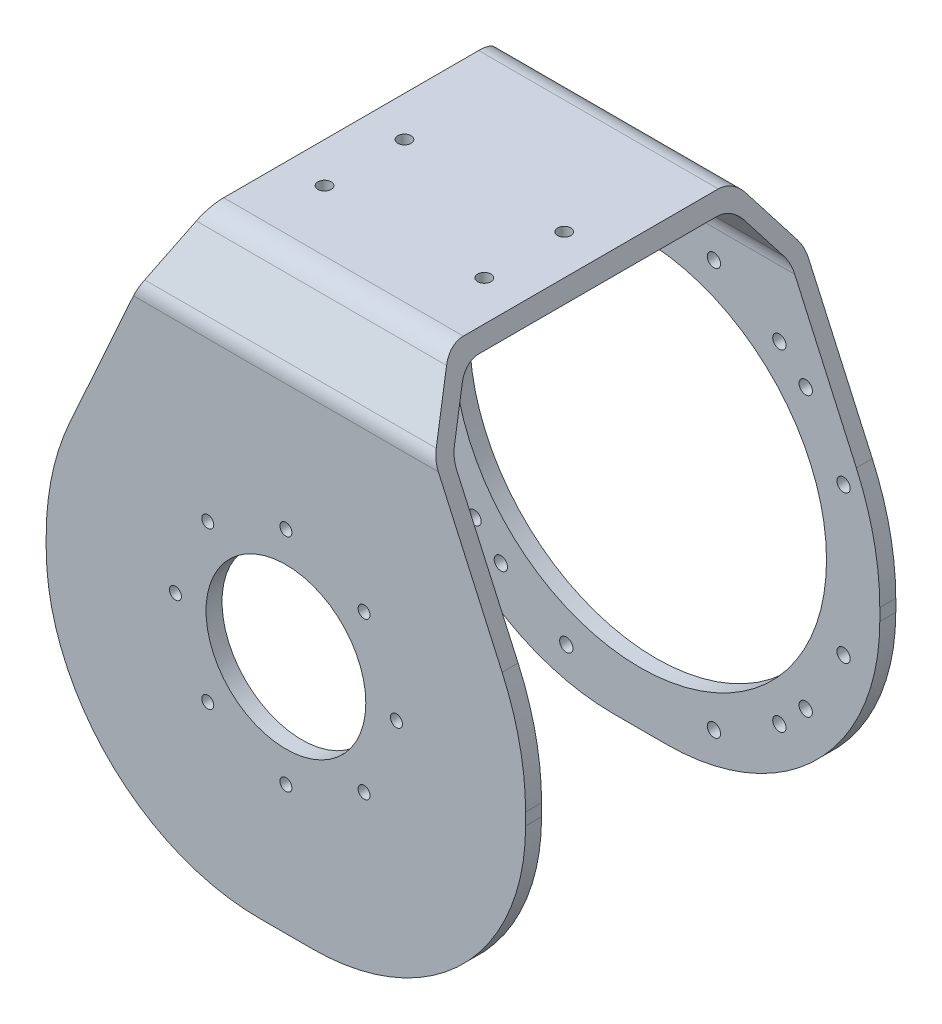
SolidWorks part; units mm, degrees
ref_plane "前视基准面" through (0, 0, 0) normal (0, 0, 1) x (1, 0, 0)
ref_plane "上视基准面" through (0, 0, 0) normal (0, 1, 0) x (1, 0, 0)
ref_plane "右视基准面" through (0, 0, 0) normal (1, 0, 0) x (0, 0, -1)
other "Configuration Table"
sketch "草图11" plane through (0, 0, 0) normal (1, 0, 0) x (0, 0, -1)
  line L0 (0, 0) -> (0, 82.4039) construction
  line L1 (-50, 200) -> (50, 200)
  line L2 (50, 200) -> (63.5, 180)
  line L3 (63.5, 180) -> (63.5, 0)
  line L4 (-63.5, 180) -> (-63.5, 0)
  line L5 (-50, 200) -> (-63.5, 180)
  point P10 (0, 200)
  dimension "D1" = 63.5
  dimension "D2" = 180
  dimension "D3" = 50
  dimension "D4" = 200
  dimension "D5" = 63.5
  dimension "D6" = 180
extrude "拉伸-薄壁1" add sketch "草图11" along normal blind 180 thin thin type one direction wall 6
sketch "草图12" plane through (0, 0, 0) normal (0, 0, 1) x (1, 0, 0)
  line L0 (90, 283.6741) -> (90, -81.1896) construction
  line L1 (180, 181.8355) -> (180, 0) construction
  line L2 (0, 181.8355) -> (0, 0) construction
  line L3 (45, 206) -> (0, 106)
  line L4 (180, 206) -> (0, 206) construction
  line L5 (0, 106) -> (0, 206)
  line L6 (0, 206) -> (0, 181.8355) construction
  line L7 (0, 206) -> (45, 206)
  line L8 (180, 106) -> (180, 206)
  line L9 (180, 206) -> (135, 206)
  line L10 (135, 206) -> (180, 106)
  circle A0 centre (90, 90) radius 85 construction
  dimension "D1" = 170
  dimension "D2" = 90
  dimension "D3" = 100
  dimension "D4" = 45
extrude "切除-拉伸1" cut sketch "草图12" against normal through all both and the other way through all
sketch "草图13" plane through (0, 0, -69.5) normal (0, 0, -1) x (-1, 0, 0)
  line L0 (-90, 90) -> (-90, 242.4141) construction
  line L1 (-90, 90) -> (-142.2916, 152.1864) construction
  line L2 (-90, 90) -> (-152.1864, 142.2916) construction
  line L3 (-90, 90) -> (-166.3791, 117.7092) construction
  line L4 (-117.7092, 166.3791) -> (-90, 90) construction
  circle A0 centre (-90, 90) radius 70
  circle A1 centre (-90, 90) radius 81.25 construction
  circle A2 centre (-117.7092, 166.3791) radius 2.5
  circle A3 centre (-142.2916, 152.1864) radius 2.5
  circle A4 centre (-152.1864, 142.2916) radius 2.5
  circle A5 centre (-166.3791, 117.7092) radius 2.5
  circle A6 centre (-13.6209, 117.7092) radius 2.5
  circle A7 centre (-27.8136, 142.2916) radius 2.5
  circle A8 centre (-37.7084, 152.1864) radius 2.5
  circle A9 centre (-62.2908, 166.3791) radius 2.5
  circle A10 centre (-62.2908, 13.6209) radius 2.5
  circle A11 centre (-37.7084, 27.8136) radius 2.5
  circle A12 centre (-27.8136, 37.7084) radius 2.5
  circle A13 centre (-13.6209, 62.2908) radius 2.5
  circle A14 centre (-166.3791, 62.2908) radius 2.5
  circle A15 centre (-152.1864, 37.7084) radius 2.5
  circle A16 centre (-142.2916, 27.8136) radius 2.5
  circle A17 centre (-117.7092, 13.6209) radius 2.5
  point P40 (-90, 90)
  dimension "D1" = 140
  dimension "D2" = 162.5
  dimension "D3" = 5
  dimension "D4" = 30
  dimension "D5" = 30
  dimension "D6" = 9.88
  dimension "D7" = 4
extrude "切除-拉伸2" cut sketch "草图13" against normal blind 50
sketch "草图14" plane through (0, 206, 0) normal (0, 1, 0) x (1, 0, 0)
  line L0 (0, 0) -> (194.3741, 0) construction
  line L1 (90, 89.7264) -> (90, -95.0261) construction
  line L2 (135, 53.189) -> (135, -53.189) construction
  line L3 (45, 53.189) -> (45, -53.189) construction
  line L4 (23.7378, -10) -> (180.4517, -10) construction
  circle A0 centre (120, 5) radius 2.5
  circle A1 centre (120, -25) radius 2.5
  circle A2 centre (60, -25) radius 2.5
  circle A3 centre (60, 5) radius 2.5
  dimension "D1" = 5
  dimension "D3" = 60
  dimension "D2" = 30
  dimension "D4" = 10
extrude "切除-拉伸3" cut sketch "草图14" against normal up to surface (6 mm away) up to face at (90, 200, 0)
sketch "草图15" plane through (0, 0, 69.5) normal (0, 0, 1) x (1, 0, 0)
  line L0 (90, 272.4002) -> (90, -73.9333) construction
  line L1 (90, 283.6741) -> (90, -81.1896) construction
  circle A0 centre (90, 90) radius 30
  circle A1 centre (90, 90) radius 41.5 construction
  circle A2 centre (90, 131.5) radius 2.25
  circle A3 centre (119.3449, 119.3449) radius 2.25
  circle A4 centre (131.5, 90) radius 2.25
  circle A5 centre (119.3449, 60.6551) radius 2.25
  circle A6 centre (90, 48.5) radius 2.25
  circle A7 centre (60.6551, 60.6551) radius 2.25
  circle A8 centre (48.5, 90) radius 2.25
  circle A9 centre (60.6551, 119.3449) radius 2.25
  point P2 (90, 90)
  point P27 (90, 90)
  dimension "D1" = 60
  dimension "D2" = 83
  dimension "D3" = 4.5
  dimension "D4" = 8
extrude "切除-拉伸4" cut sketch "草图15" against normal up to surface (6 mm away) up to face at (90, 95.3333, 63.5)
fillet "圆角1" radius 100 4 edges at (180, 106, -66.5) (0, 106, -66.5) (0, 106, 66.5) (180, 106, 66.5)
fillet "圆角2" radius 80 4 edges at (0, 0, 66.5) (180, 0, 66.5) (180, 0, -66.5) (0, 0, -66.5)
fillet "圆角3" radius 10 8 edges at (90, 180, 63.5) (90, 200, 50) (90, 180, -63.5) (90, 200, -50) (90, 181.8355, 69.5) (90, 206, 53.189) (90, 181.8355, -69.5) (90, 206, -53.189)
